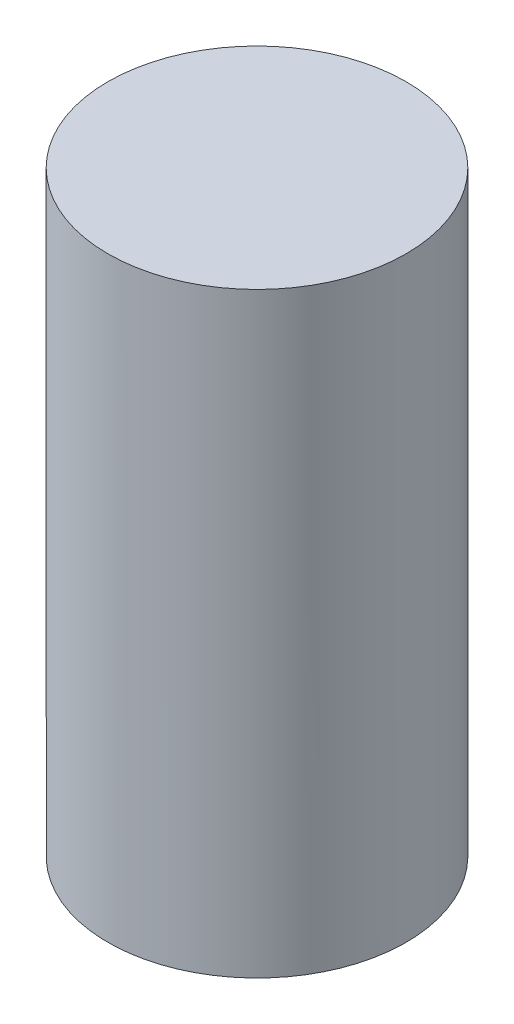
SolidWorks part; units mm, degrees
ref_plane "Front Plane" through (0, 0, 0) normal (0, 0, 1) x (1, 0, 0)
ref_plane "Top Plane" through (0, 0, 0) normal (0, 1, 0) x (1, 0, 0)
ref_plane "Right Plane" through (0, 0, 0) normal (1, 0, 0) x (0, 0, -1)
sketch "Sketch1" plane through (0, 0, 0) normal (0, 1, 0) x (1, 0, 0)
  line L0 (0, 0) -> (0, 5) construction
  line L1 (0, 0) -> (1.5, 0) construction
  line L2 (1.5, 0) -> (1.5, 4.7697) construction
  line L5 (1.5, -2.2361) -> (1.5, 2.2361)
  line L6 (-1.5, -2.2361) -> (-1.5, 2.2361)
  line L7 (-3.5, 0) -> (-1.5, 0) construction
  circle A0 centre (0, 0) radius 5
  arc A1 (-2.3333, 2.6087) -> (-2.3333, -2.6087) centre (0, 0) ccw
  arc A2 (2.3333, -2.6087) -> (2.3333, 2.6087) centre (0, 0) ccw
  arc A3 (2.3333, 2.6087) -> (1.5, 2.2361) centre (2, 2.2361) ccw
  arc A4 (2.3333, -2.6087) -> (1.5, -2.2361) centre (2, -2.2361) cw
  arc A5 (-1.5, -2.2361) -> (-2.3333, -2.6087) centre (-2, -2.2361) cw
  arc A6 (-1.5, 2.2361) -> (-2.3333, 2.6087) centre (-2, 2.2361) ccw
  point P12 (1.5, 3.1623)
  point P15 (1.5, -3.1623)
  point P18 (-1.5, -3.1623)
  point P21 (-1.5, 3.1623)
  dimension "D1" = 10
  dimension "D5" = 7
  dimension "D3" = 0.5
  dimension "D2" = 1.5
extrude "Boss-Extrude1" add sketch "Sketch1" along normal blind 15
sketch "Sketch2" plane through (0, 0, 0) normal (0, -1, 0) x (1, 0, 0)
  line L0 (0, 0) -> (1.5, 0) construction
  line L2 (1.5, 0) -> (3.5, 0) construction
  line L3 (0, 0) -> (-1.5, 0) construction
  line L5 (-1.5, 0) -> (-3.5, 0) construction
  line L6 (0, 0) -> (0, 5) construction
  line L7 (-1.5, 2.2361) -> (-1.5, -2.2361) construction
  circle A0 centre (0, 0) radius 5
  circle A1 centre (-2.5, 0) radius 0.8
  circle A2 centre (0, 0) radius 5 construction
  circle A3 centre (2.5, 0) radius 0.8
  arc A4 (-2.3333, 2.6087) -> (-2.3333, -2.6087) centre (0, 0) ccw construction
  dimension "D1" = 1.6
extrude "Boss-Extrude2" add sketch "Sketch2" along normal blind 2
sketch "Sketch3" plane through (0, 15, 0) normal (0, 1, 0) x (1, 0, 0)
  circle A0 centre (0, 0) radius 5
  circle A1 centre (0, 0) radius 5 construction
extrude "Boss-Extrude3" add sketch "Sketch3" along normal blind 3
